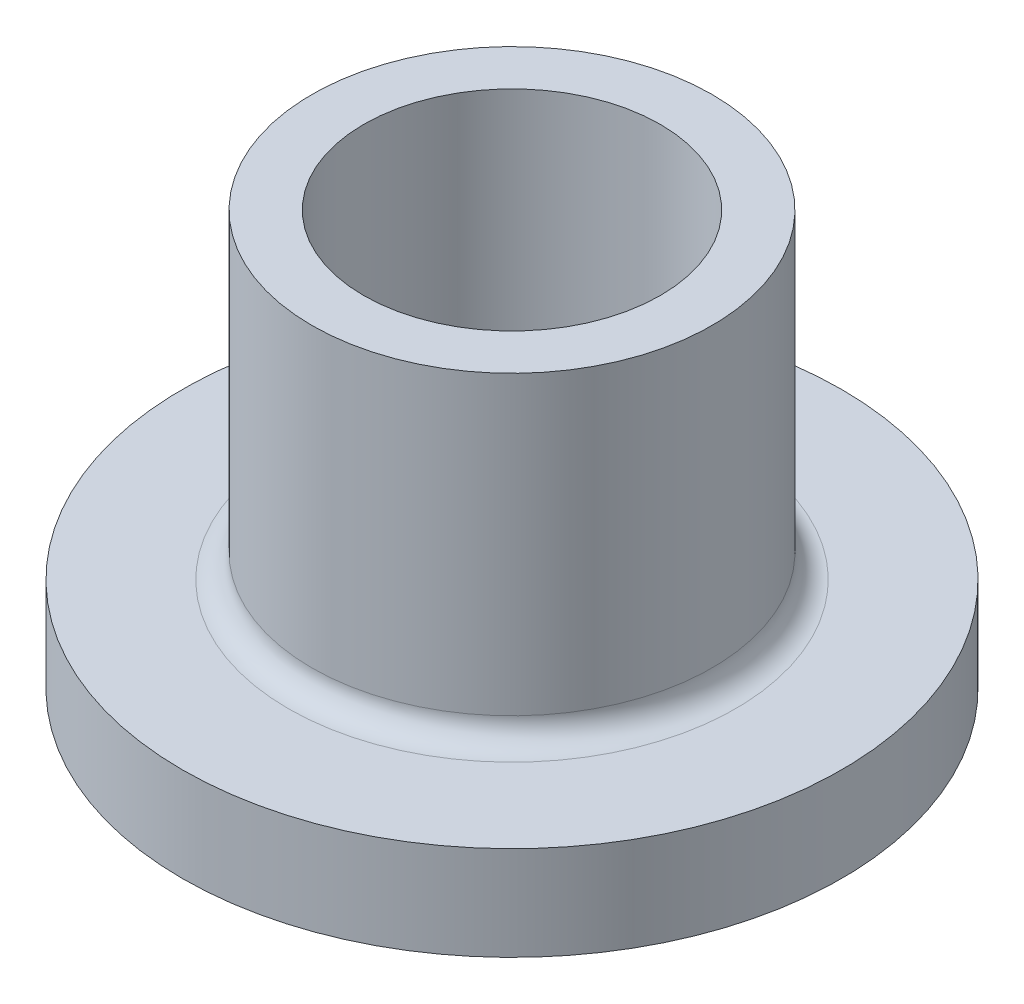
SolidWorks part; units mm, degrees
ref_plane "前视基准面" through (0, 0, 0) normal (0, 0, 1) x (1, 0, 0)
ref_plane "上视基准面" through (0, 0, 0) normal (0, 1, 0) x (1, 0, 0)
ref_plane "右视基准面" through (0, 0, 0) normal (1, 0, 0) x (0, 0, -1)
sketch "草图1" plane through (0, 0, 0) normal (0, 1, 0) x (1, 0, 0)
  circle A0 centre (0, 0) radius 7
  dimension "D1" = 14
extrude "凸台-拉伸1" add sketch "草图1" along normal blind 2
sketch "草图2" plane through (0, 2, 0) normal (0, 1, 0) x (1, 0, 0)
  circle A0 centre (0, 0) radius 4.25
  dimension "D1" = 8.5
extrude "凸台-拉伸2" add sketch "草图2" along normal blind 6.8
sketch "草图3" plane through (0, 8.8, 0) normal (0, 1, 0) x (1, 0, 0)
  circle A0 centre (0, 0) radius 3.15
  dimension "D1" = 6.3
extrude "切除-拉伸1" cut sketch "草图3" against normal up to next
fillet "圆角1" radius 0.5 1 edges at (0, 2, 4.25)
